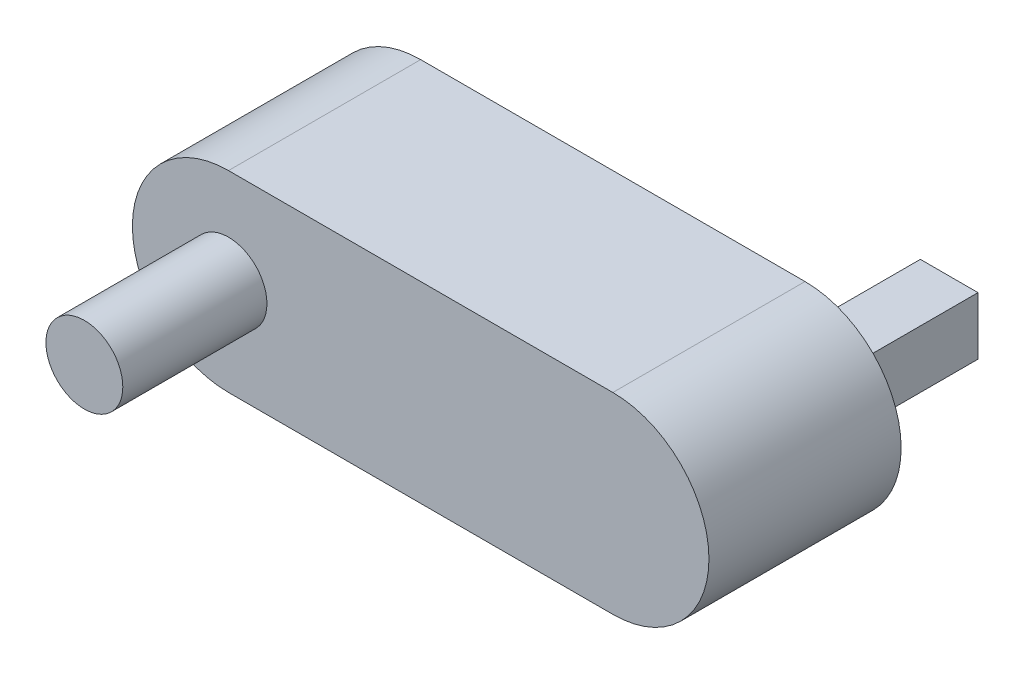
SolidWorks part; units mm, degrees
ref_plane "前视基准面" through (0, 0, 0) normal (0, 0, 1) x (1, 0, 0)
ref_plane "上视基准面" through (0, 0, 0) normal (0, 1, 0) x (1, 0, 0)
ref_plane "右视基准面" through (0, 0, 0) normal (1, 0, 0) x (0, 0, -1)
other "Configuration Table"
sketch "草图1" plane through (0, 0, 0) normal (0, 0, 1) x (1, 0, 0)
  line L0 (0, 0) -> (40, 0) construction
  line L1 (0, 10) -> (40, 10)
  line L2 (0, -10) -> (40, -10)
  arc A0 (0, 10) -> (0, -10) centre (0, 0) ccw
  arc A1 (40, -10) -> (40, 10) centre (40, 0) ccw
  point P3 (20, 0)
  dimension "D2" = 10
  dimension "D1" = 40
extrude "凸台-拉伸1" add sketch "草图1" along normal mid plane 20
sketch "草图2" plane through (0, 0, 10) normal (0, 0, 1) x (1, 0, 0)
  circle A0 centre (0, 0) radius 4
  dimension "D1" = 8
extrude "凸台-拉伸2" add sketch "草图2" along normal blind 15
sketch "草图3" plane through (0, 0, -10) normal (0, 0, -1) x (-1, 0, 0)
  line L0 (-40, 10) -> (0, 10) construction
  line L1 (-43, -3) -> (-37, -3)
  line L2 (-43, -3) -> (-43, 3)
  line L3 (-43, 3) -> (-37, 3)
  line L4 (-37, -3) -> (-37, 3)
  line L5 (-43, -3) -> (-37, 3) construction
  line L6 (-43, 3) -> (-37, -3) construction
  point P0 (-40, 0)
  dimension "D1" = 40
  dimension "D2" = 6
  dimension "D3" = 6
  dimension "D4" = 10
extrude "凸台-拉伸3" add sketch "草图3" along normal blind 15
